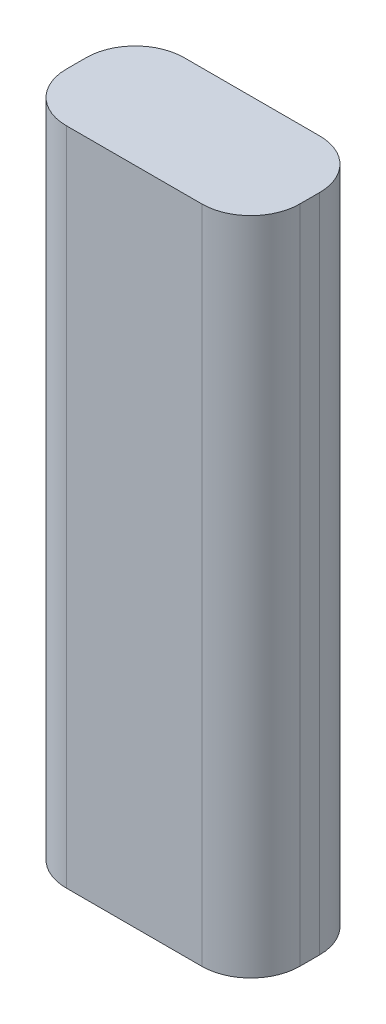
SolidWorks part; units mm, degrees
ref_plane "正面" through (0, 0, 0) normal (0, 0, 1) x (1, 0, 0)
ref_plane "平面" through (0, 0, 0) normal (0, 1, 0) x (1, 0, 0)
ref_plane "右側面" through (0, 0, 0) normal (1, 0, 0) x (0, 0, -1)
sketch "ｽｹｯﾁ1" plane through (0, 0, 0) normal (0, 0, 1) x (1, 0, 0)
  line L1 (23.835, -67.395) -> (-23.835, -67.395)
  line L2 (23.835, -67.395) -> (23.835, 67.395)
  line L3 (23.835, 67.395) -> (-23.835, 67.395)
  line L4 (-23.835, -67.395) -> (-23.835, 67.395)
  line L5 (23.835, -67.395) -> (-23.835, 67.395) construction
  line L6 (23.835, 67.395) -> (-23.835, -67.395) construction
  point P0 (0, 0)
  dimension "D1" = 134.79
  dimension "D2" = 47.67
extrude "ﾎﾞｽ - 押し出し1" add sketch "ｽｹｯﾁ1" along normal blind 24.06
fillet "ﾌｨﾚｯﾄ1" radius 10 4 edges at (23.835, 0, 0) (23.835, 0, 24.06) (-23.835, 0, 24.06) (-23.835, 0, 0)
